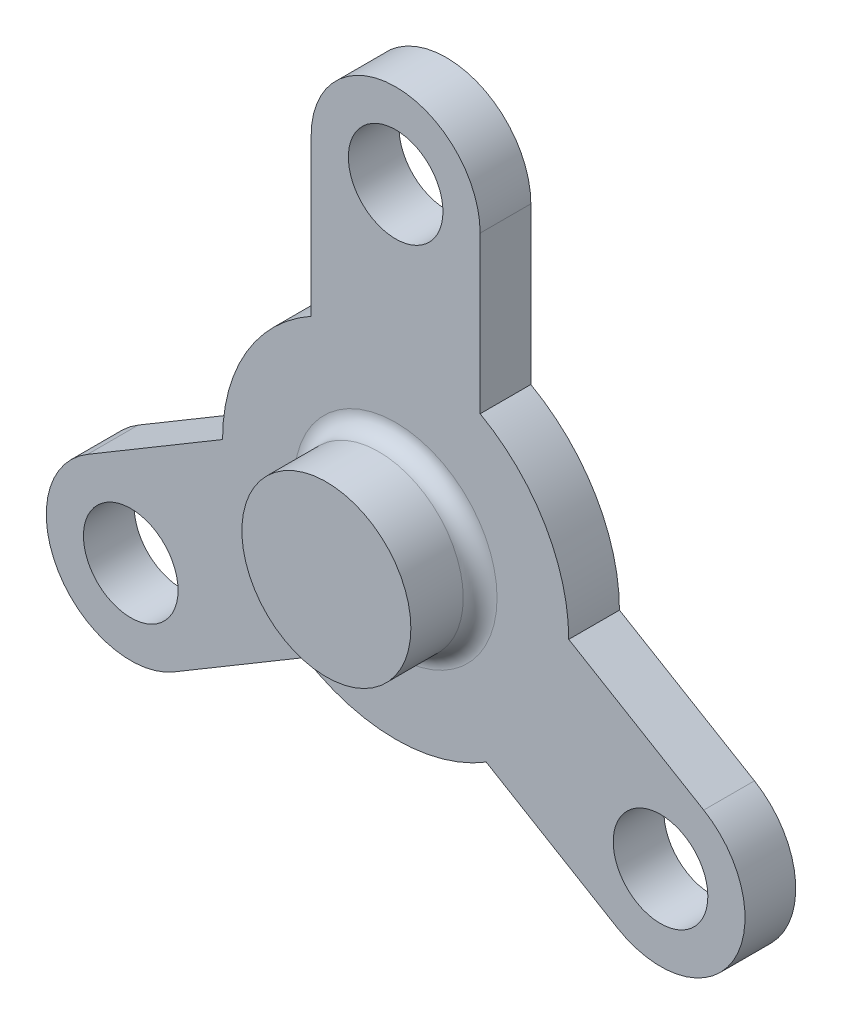
SolidWorks part; units mm, degrees
ref_plane "Alzado" through (0, 0, 0) normal (0, 0, 1) x (1, 0, 0)
ref_plane "Planta" through (0, 0, 0) normal (0, 1, 0) x (1, 0, 0)
ref_plane "Vista lateral" through (0, 0, 0) normal (1, 0, 0) x (0, 0, -1)
sketch "Croquis1" plane through (0, 0, 0) normal (0, 0, 1) x (1, 0, 0)
  line L0 (-18.2318, -4.7531) -> (-10.2435, 0)
  line L1 (-13.1183, -13.3469) -> (-5.359, -8.7299)
  line L2 (13.1183, -13.3469) -> (5.359, -8.7299)
  line L3 (-13.1183, -13.3469) -> (-18.2318, -4.7531)
  line L7 (13.1183, -13.3469) -> (18.2318, -4.7531)
  line L11 (-5, 18.2) -> (5, 18.2)
  line L15 (18.2318, -4.7531) -> (10.2435, 0)
  line L16 (-5, 18.2) -> (-5, 8.9404)
  line L17 (5, 18.2) -> (5, 8.9404)
  circle A0 centre (0, 18.2) radius 5
  circle A1 centre (15.6751, -9.05) radius 5
  circle A2 centre (-15.6751, -9.05) radius 5
  circle A3 centre (0, 0) radius 10.2435
  dimension "D7" = 10
  dimension "D8" = 10
  dimension "D9" = 10
  dimension "D1" = 90
  dimension "D2" = 90
  dimension "D3" = 90
  dimension "D4" = 18.1
  dimension "D5" = 18.1
  dimension "D6" = 18.2
  dimension "D10" = 90
  dimension "D11" = 90
  dimension "D12" = 90
extrude "Saliente-Extruir1" add sketch "Croquis1" along normal blind 3 contours L3 A2 | L3 A2 | A3 L0 A2 L1 | A3 | A3 L2 A1 L15 | A3 L17 A0 L16 | L11 A0 | L11 A0
sketch "Croquis2" plane through (0, 0, 3) normal (0, 0, 1) x (1, 0, 0)
  circle A0 centre (0, 18.2) radius 2.8
  circle A1 centre (15.6751, -9.05) radius 2.8
  circle A2 centre (-15.6751, -9.05) radius 2.8
  dimension "D1" = 5.6
  dimension "D2" = 5.6
  dimension "D3" = 5.6
extrude "Cortar-Extruir3" cut sketch "Croquis2" against normal blind 5.5
sketch "Croquis3" plane through (0, 0, 3) normal (0, 0, 1) x (1, 0, 0)
  circle A0 centre (0, 0) radius 5
  dimension "D1" = 10
extrude "Saliente-Extruir2" add sketch "Croquis3" along normal blind 4.1
fillet "Redondeo1" radius 1 1 edges at (5, 0, 3)
